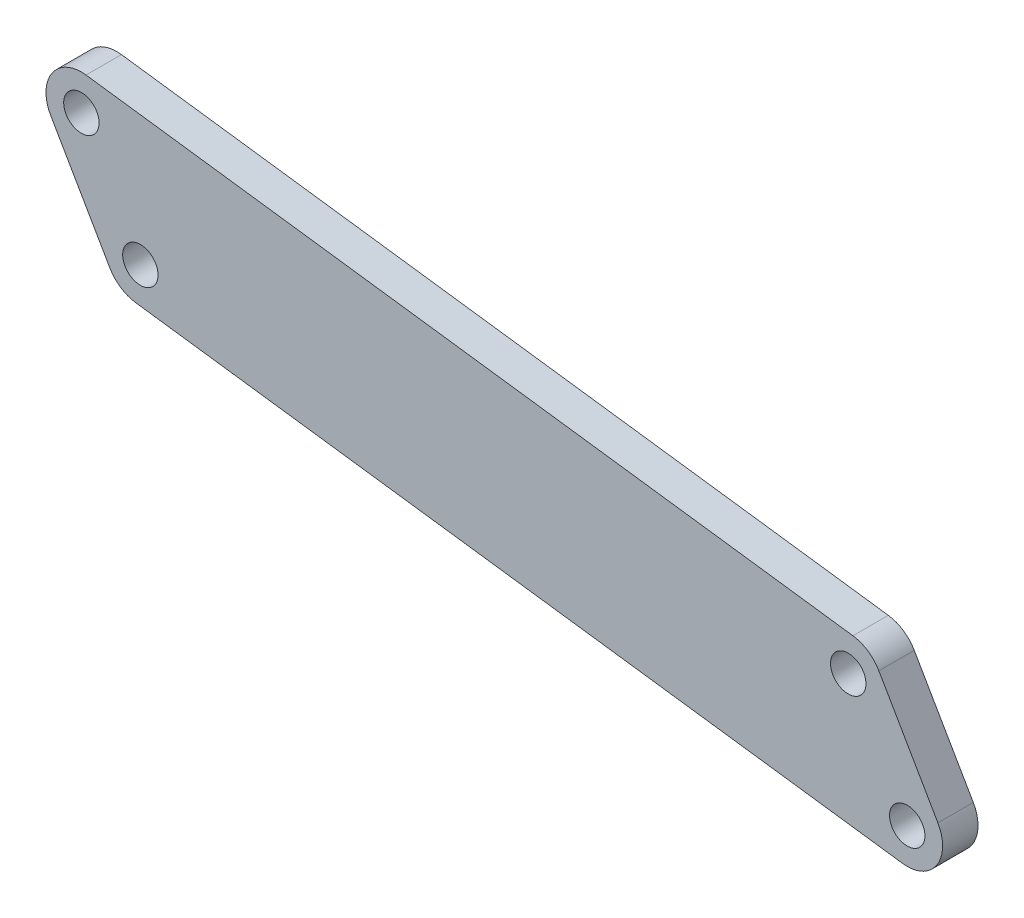
SolidWorks part; units mm, degrees
ref_plane "Front Plane" through (0, 0, 0) normal (0, 0, 1) x (1, 0, 0)
ref_plane "Top Plane" through (0, 0, 0) normal (0, 1, 0) x (1, 0, 0)
ref_plane "Right Plane" through (0, 0, 0) normal (1, 0, 0) x (0, 0, -1)
sketch "Sketch1" plane through (0, 0, 0) normal (0, 0, 1) x (1, 0, 0)
  line L0 (0, 0) -> (-60, 0)
  line L1 (-60, 0) -> (-65, 8.6603)
  line L2 (0, 0) -> (5, -8.6603)
  dimension "D1" = 60
  dimension "D2" = 10
  dimension "D3" = 10
  dimension "D4" = 120
  dimension "D5" = 120
sketch "Sketch2" plane through (0, 0, 0) normal (0, 0, 1) x (1, 0, 0)
  line L0 (-64.6038, 11.634) -> (0.3962, 2.9737)
  line L1 (2.5981, 1.5) -> (7.5981, -7.1603)
  line L2 (4.6038, -11.634) -> (-60.3962, -2.9737)
  line L3 (-62.5981, -1.5) -> (-67.5981, 7.1603)
  circle A0 centre (-60, 0) radius 1.5
  circle A1 centre (-65, 8.6603) radius 1.5
  arc A2 (-64.6038, 11.634) -> (-67.5981, 7.1603) centre (-65, 8.6603) ccw
  arc A3 (-62.5981, -1.5) -> (-60.3962, -2.9737) centre (-60, 0) ccw
  circle A4 centre (0, 0) radius 1.5
  circle A5 centre (5, -8.6603) radius 1.5
  arc A6 (2.5981, 1.5) -> (0.3962, 2.9737) centre (0, 0) ccw
  arc A7 (4.6038, -11.634) -> (7.5981, -7.1603) centre (5, -8.6603) ccw
  dimension "D1" = 3
  dimension "D2" = 3
  dimension "D3" = 3
  dimension "D4" = 3
  dimension "D5" = 6
  dimension "D6" = 6
  dimension "D7" = 6
  dimension "D8" = 6
extrude "Boss-Extrude1" add sketch "Sketch2" along normal blind 3
